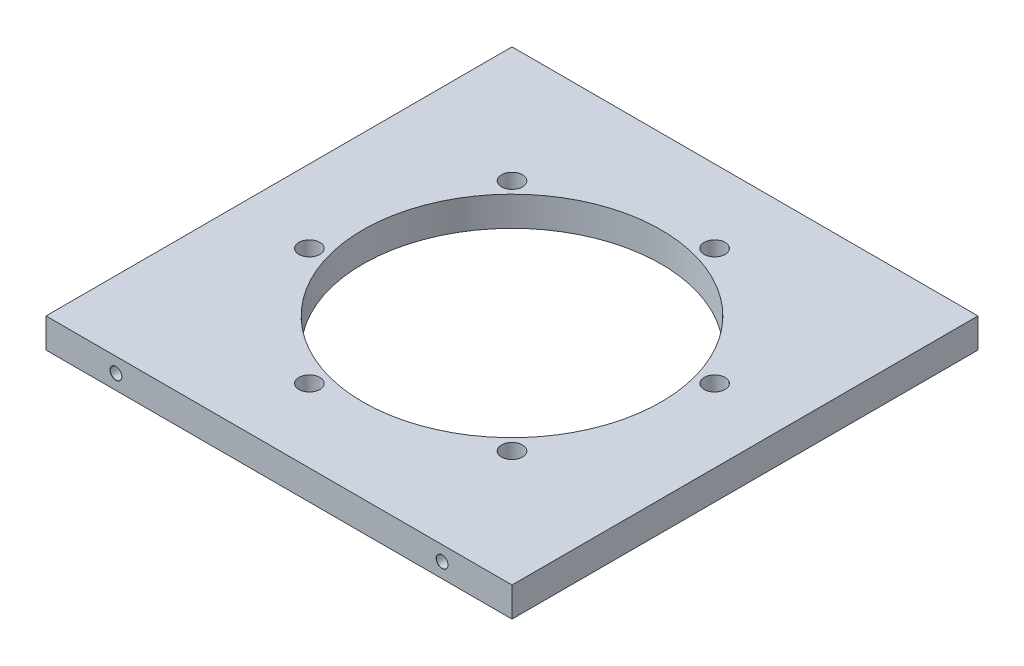
SolidWorks part; units mm, degrees
material "6061 Alloy"
ref_plane "Front Plane" through (0, 0, 0) normal (0, 0, 1) x (1, 0, 0)
ref_plane "Top Plane" through (0, 0, 0) normal (0, 1, 0) x (1, 0, 0)
ref_plane "Right Plane" through (0, 0, 0) normal (1, 0, 0) x (0, 0, -1)
sketch "Sketch1" plane through (0, 0, 0) normal (0, 1, 0) x (1, 0, 0)
  line L1 (-50, -50) -> (50, -50)
  line L2 (-50, -50) -> (-50, 50)
  line L3 (-50, 50) -> (50, 50)
  line L4 (50, -50) -> (50, 50)
  line L5 (-50, -50) -> (50, 50) construction
  line L6 (-50, 50) -> (50, -50) construction
  circle A1 centre (0, 0) radius 39.5
  arc A5 (-25.1023, 25.1023) -> (9.1881, 34.2904) centre (0, 0) cw
  arc A7 (9.1881, 34.2904) -> (-34.2904, -9.1881) centre (0, 0) ccw
  arc A9 (-34.2904, -9.1881) -> (-9.1881, -34.2904) centre (0, 0) ccw
  arc A11 (-9.1881, -34.2904) -> (25.1023, -25.1023) centre (0, 0) ccw
  circle A13 centre (0, 0) radius 32
  arc A14 (25.1023, -25.1023) -> (34.2904, 9.1881) centre (0, 0) ccw
extrude "Boss-Extrude3" add sketch "Sketch1" along normal blind 6.35
hole_wizard "M4 Clearance Hole2" positions "Sketch6" profile "Sketch7" hole size "M4" standard "ANSI Metric" end condition through all
sketch "Sketch6" plane through (0, 0, 0) normal (0, -1, 0) x (-1, 0, 0)
  point P0 (-9.1881, 34.2904)
  point P3 (25.1023, 25.1023)
  point P6 (34.2904, -9.1881)
  point P9 (9.1881, -34.2904)
  point P12 (-25.1023, -25.1023)
  point P15 (-34.2904, 9.1881)
sketch "Sketch7" plane through (9.1881, 0, -34.2904) normal (1, 0, 0) x (0, 0, -1)
  line L0 (0, 0) -> (0, 6.35)
  line L1 (0, 6.35) -> (2.25, 6.35)
  line L2 (2.25, 6.35) -> (2.25, 0.025)
  line L3 (2.25, 0.025) -> (2.275, 0)
  line L5 (2.275, 0) -> (0, 0)
  line L6 (-2.25, 0.025) -> (-2.275, 0) construction
  line L11 (0, -6.35) -> (0, 107.95) construction
  dimension "Thru Hole Dia." = 4.5
  dimension "Thru Hole Depth" = 6.35
  dimension "Near C'Sink Dia." = 4.55
  dimension "Near C'Sink Angle" = 90
sketch "Sketch13" plane through (0, 6.35, 0) normal (0, 1, 0) x (1, 0, 0)
  line L0 (-50, -50) -> (-46.1091, -46.1091)
  line L1 (-46.1091, -46.1091) -> (-68.3017, -23.9166)
  line L2 (-46.1091, -46.1091) -> (-23.9166, -68.3017)
sketch "Sketch16" plane through (0, 6.35, 0) normal (0, 1, 0) x (1, 0, 0)
  line L0 (-50, -50) -> (-55, -50)
  line L1 (-50, -50) -> (50, -50) construction
  line L2 (-55, -50) -> (-55, -70)
  line L3 (-50, -50) -> (-75, -50)
  line L4 (-75, -50) -> (-75, -70)
  line L5 (-75, -70) -> (-55, -70)
  line L6 (-50, 50) -> (-55, 50)
  line L7 (-50, 50) -> (50, 50) construction
  line L8 (50, 50) -> (55, 50)
  line L9 (50, -50) -> (55, -50)
  line L11 (-55, 50) -> (-75, 50)
  line L12 (-55, 50) -> (-55, 70)
  line L13 (-55, 70) -> (-75, 70)
  line L14 (-75, 50) -> (-75, 70)
  line L15 (55, 50) -> (75, 50)
  line L16 (55, 50) -> (55, 70)
  line L17 (55, 70) -> (75, 70)
  line L18 (75, 50) -> (75, 70)
  line L19 (55, -50) -> (75, -50)
  line L20 (55, -50) -> (55, -70)
  line L21 (55, -70) -> (75, -70)
  line L22 (75, -50) -> (75, -70)
sketch "Sketch23" plane through (0, 6.35, 0) normal (0, 1, 0) x (1, 0, 0)
  line L0 (-50, -50) -> (-50, -55)
  line L1 (-50, -50) -> (-50, 50) construction
  line L2 (-50, 50) -> (-50, 55)
  line L3 (85, 50) -> (50, 55)
  line L4 (-50, 50) -> (50, 50) construction
  line L5 (50, -50) -> (50, 50) construction
  line L6 (50, -50) -> (50, -55)
  line L8 (-50, 55) -> (-70, 55)
  line L9 (-50, 55) -> (-50, 75)
  line L10 (-50, 75) -> (-70, 75)
  line L11 (-70, 55) -> (-70, 75)
  line L12 (50, 55) -> (70, 55)
  line L13 (50, 55) -> (50, 75)
  line L14 (50, 75) -> (70, 75)
  line L15 (70, 55) -> (70, 75)
  line L16 (50, -55) -> (70, -55)
  line L17 (50, -55) -> (50, -75)
  line L18 (50, -75) -> (70, -75)
  line L19 (70, -55) -> (70, -75)
  line L20 (-50, -55) -> (-70, -55)
  line L21 (-50, -55) -> (-50, -75)
  line L22 (-50, -75) -> (-70, -75)
  line L23 (-70, -55) -> (-70, -75)
sketch "Sketch24" plane through (0, 0, 50) normal (0, 0, 1) x (1, 0, 0)
  line L0 (-50, 3.175) -> (-35, 3.175)
  line L1 (-50, 6.35) -> (-50, 0) construction
  line L2 (50, 3.175) -> (35, 3.175)
  line L3 (50, 6.35) -> (50, 0) construction
hole_wizard "Tap Drill for M3x0.5 Tap2" positions "Sketch27" profile "Sketch28" hole size "M3x0.5" standard "ANSI Metric"
sketch "Sketch27" plane through (0, 0, 50) normal (0, 0, 1) x (1, 0, 0)
  point P0 (-35, 3.175)
  point P3 (35, 3.175)
sketch "Sketch28" plane through (-35, 3.175, 50) normal (1, 0, 0) x (0, -1, 0)
  line L0 (0, 0) -> (0, 10)
  line L1 (0, 10) -> (1.25, 9.2489)
  line L2 (1.25, 9.2489) -> (1.25, 0.025)
  line L3 (1.25, 0.025) -> (1.275, 0)
  line L5 (1.275, 0) -> (0, 0)
  line L6 (-1.25, 0.025) -> (-1.275, 0) construction
  line L10 (0, 10) -> (-1.25, 9.2489) construction
  line L11 (0, -6.35) -> (0, 107.95) construction
  dimension "Hole Dia." = 2.5
  dimension "Hole Depth" = 10
  dimension "Near C'Sink Dia." = 2.55
  dimension "Near C'Sink Angle" = 90
  dimension "Drill Angle" = 118
sketch "Sketch29" plane through (0, 0, -50) normal (0, 0, -1) x (-1, 0, 0)
  line L0 (-50, 3.175) -> (-35, 3.175)
  line L1 (50, 3.175) -> (35, 3.175)
hole_wizard "Tap Drill for M3x0.5 Tap3" positions "Sketch30" profile "Sketch31" hole size "M3x0.5" standard "ANSI Metric"
sketch "Sketch30" plane through (0, 0, -50) normal (0, 0, -1) x (-1, 0, 0)
  point P0 (-35, 3.175)
  point P3 (35, 3.175)
sketch "Sketch31" plane through (35, 3.175, -50) normal (1, 0, 0) x (0, 1, 0)
  line L0 (0, 0) -> (0, 10)
  line L1 (0, 10) -> (1.25, 9.2489)
  line L2 (1.25, 9.2489) -> (1.25, 0.025)
  line L3 (1.25, 0.025) -> (1.275, 0)
  line L5 (1.275, 0) -> (0, 0)
  line L6 (-1.25, 0.025) -> (-1.275, 0) construction
  line L10 (0, 10) -> (-1.25, 9.2489) construction
  line L11 (0, -6.35) -> (0, 107.95) construction
  dimension "Hole Dia." = 2.5
  dimension "Hole Depth" = 10
  dimension "Near C'Sink Dia." = 2.55
  dimension "Near C'Sink Angle" = 90
  dimension "Drill Angle" = 118
